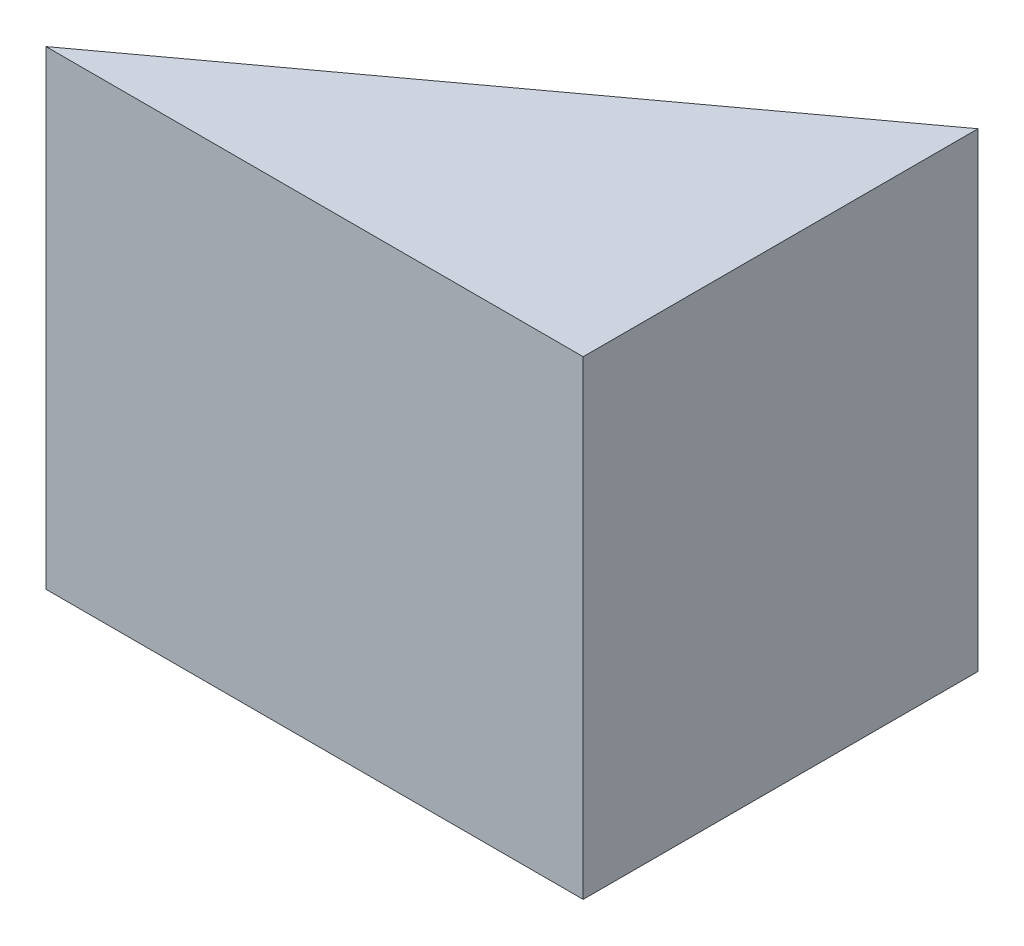
SolidWorks part; units mm, degrees
material "Plain Carbon Steel"
ref_plane "Front Plane" through (0, 0, 0) normal (0, 0, 1) x (1, 0, 0)
ref_plane "Top Plane" through (0, 0, 0) normal (0, 1, 0) x (1, 0, 0)
ref_plane "Right Plane" through (0, 0, 0) normal (1, 0, 0) x (0, 0, -1)
sketch "Sketch2" plane through (0, 0, 0) normal (0, 1, 0) x (1, 0, 0)
  line L0 (-60.0281, 18.185) -> (39.9719, 18.185)
  line L1 (39.9719, 18.185) -> (39.9719, 91.685)
  line L2 (39.9719, 91.685) -> (-60.0281, 18.185)
extrude "Boss-Extrude2" add sketch "Sketch2" along normal blind 87.5
